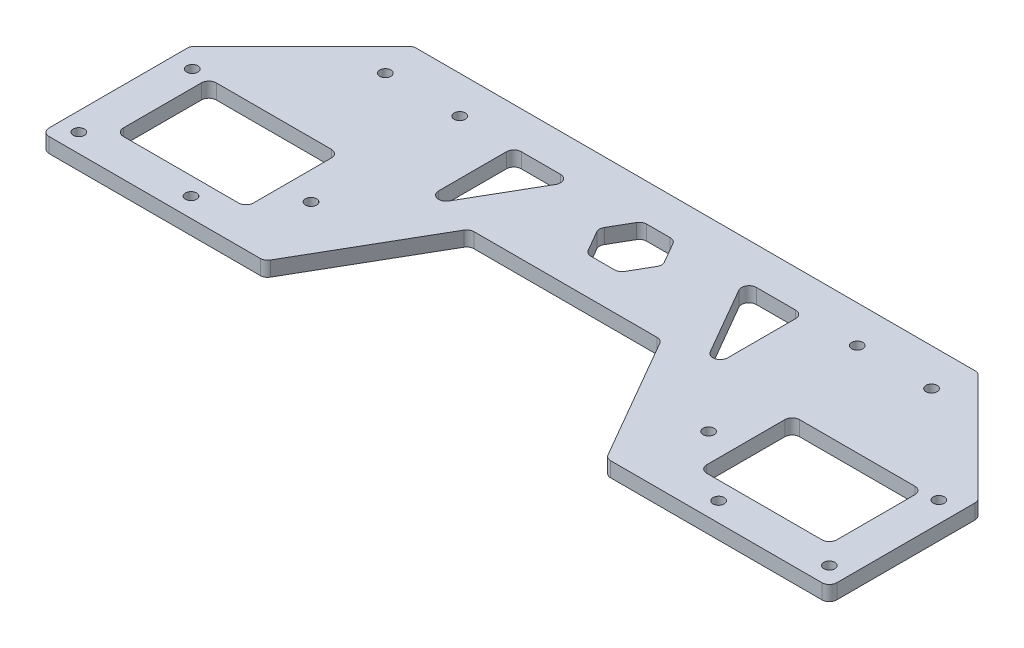
SolidWorks part; units mm, degrees
ref_plane "前视基准面" through (0, 0, 0) normal (0, 0, 1) x (1, 0, 0)
ref_plane "上视基准面" through (0, 0, 0) normal (0, 1, 0) x (1, 0, 0)
ref_plane "右视基准面" through (0, 0, 0) normal (1, 0, 0) x (0, 0, -1)
sketch "草图1" plane through (0, 0, 0) normal (0, 1, 0) x (1, 0, 0)
  line L0 (0, 0) -> (51.5855, 0)
  line L1 (51.5855, 0) -> (71.7927, -35)
  line L2 (71.7927, -35) -> (131.7927, -35)
  line L3 (131.7927, -35) -> (131.7927, 5)
  line L4 (131.7927, 5) -> (101.7927, 35)
  line L5 (101.7927, 35) -> (-50.2073, 35)
  line L6 (-50.2073, 35) -> (-80.2073, 5)
  line L7 (-80.2073, 5) -> (-80.2073, -35)
  line L8 (-80.2073, -35) -> (-20.2073, -35)
  line L9 (-20.2073, -35) -> (0, 0)
  dimension "D2" = 60
  dimension "D3" = 60
  dimension "D4" = 35
  dimension "D5" = 60
  dimension "D6" = 60
  dimension "D7" = 45
  dimension "D8" = 45
  dimension "D9" = 30
  dimension "D10" = 30
  dimension "D11" = 35
  dimension "D12" = 35
  dimension "D13" = 92
extrude "凸台-拉伸1" add sketch "草图1" along normal blind 4
sketch "草图2" plane through (0, 4, 0) normal (0, 1, 0) x (1, 0, 0)
  line L0 (-80.2073, -35) -> (-20.2073, -35) construction
  line L1 (-70.2073, -25) -> (-35.2073, -25)
  line L2 (-70.2073, -25) -> (-70.2073, 0)
  line L3 (-70.2073, 0) -> (-35.2073, 0)
  line L4 (-35.2073, -25) -> (-35.2073, 0)
  line L5 (121.7927, -25) -> (86.7927, -25)
  line L6 (121.7927, -25) -> (121.7927, 0)
  line L7 (121.7927, 0) -> (86.7927, 0)
  line L8 (86.7927, -25) -> (86.7927, 0)
  line L9 (-80.2073, 5) -> (-80.2073, -35) construction
  line L10 (71.7927, -35) -> (131.7927, -35) construction
  line L11 (131.7927, -35) -> (131.7927, 5) construction
  dimension "D1" = 10
  dimension "D2" = 10
  dimension "D3" = 10
  dimension "D4" = 10
  dimension "D5" = 35
  dimension "D6" = 25
  dimension "D7" = 35
  dimension "D8" = 25
extrude "切除-拉伸1" cut sketch "草图2" against normal blind 4
sketch "草图3" plane through (0, 4, 0) normal (0, 1, 0) x (1, 0, 0)
  line L0 (-80.2073, -35) -> (-20.2073, -35) construction
  line L1 (-80.2073, 5) -> (-80.2073, -35) construction
  line L2 (25.7927, 119.2379) -> (25.7927, -49.2379) construction
  line L3 (101.7927, 35) -> (-50.2073, 35) construction
  circle A0 centre (-75.2073, -30) radius 1.5
  circle A1 centre (-45.2073, -29.7968) radius 1.5
  circle A2 centre (-74.6686, 0) radius 1.5
  circle A3 centre (126.254, 0) radius 1.5
  circle A4 centre (96.7927, -29.7968) radius 1.5
  circle A5 centre (126.7927, -30) radius 1.5
  circle A6 centre (-27.7073, -15) radius 1.5
  circle A7 centre (-47.7073, 25) radius 1.5
  circle A8 centre (-27.7073, 25) radius 1.5
  circle A9 centre (79.2927, -15) radius 1.5
  circle A10 centre (99.2927, 25) radius 1.5
  circle A11 centre (79.2927, 25) radius 1.5
  point P32 (25.7927, 35)
  point P33 (25.7927, 35)
  dimension "D1" = 5
  dimension "D2" = 5
  dimension "D3" = 30
  dimension "D4" = 30
  dimension "D5" = 20
  dimension "D6" = 52.5
  dimension "D7" = 3
  dimension "D9" = 10
  dimension "D10" = 20
  dimension "D11" = 32.5
  dimension "D8" = 10
extrude "切除-拉伸2" cut sketch "草图3" against normal blind 4
sketch "草图4" plane through (0, 4, 0) normal (0, 1, 0) x (1, 0, 0)
  line L0 (0, 0) -> (51.5855, 0) construction
  line L1 (34.453, 17.5) -> (30.1229, 25)
  line L2 (30.1229, 25) -> (21.4626, 25)
  line L3 (21.4626, 25) -> (17.1325, 17.5)
  line L4 (17.1325, 17.5) -> (21.4626, 10)
  line L5 (21.4626, 10) -> (30.1229, 10)
  line L6 (30.1229, 10) -> (34.453, 17.5)
  line L7 (101.7927, 35) -> (-50.2073, 35) construction
  line L8 (48.6987, 25) -> (64.6987, 25)
  line L9 (64.6987, -2.7128) -> (48.6987, 25)
  line L10 (64.6987, 25) -> (64.6987, -2.7128)
  line L11 (51.5855, 0) -> (71.7927, -35) construction
  line L12 (25.7927, 74.7356) -> (25.7927, -40.8365) construction
  line L13 (-13.1132, 25) -> (-13.1132, -2.7128)
  line L14 (-13.1132, -2.7128) -> (2.8868, 25)
  line L15 (2.8868, 25) -> (-13.1132, 25)
  circle A0 centre (25.7927, 17.5) radius 7.5 construction
  point P12 (25.7927, 0)
  dimension "D1" = 10
  dimension "D2" = 10
  dimension "D3" = 0
  dimension "D4" = 10
  dimension "D5" = 16
extrude "切除-拉伸3" cut sketch "草图4" against normal blind 4
fillet "圆角1" radius 2 30 edges at (21.4626, 2, -10) (30.1229, 2, -10) (34.453, 2, -17.5) (30.1229, 2, -25) (21.4626, 2, -25) (17.1325, 2, -17.5) (-13.1132, 2, 2.7128) (2.8868, 2, -25) (-13.1132, 2, -25) (48.6987, 2, -25) (64.6987, 2, 2.7128) (64.6987, 2, -25) (121.7927, 2, 0) (121.7927, 2, 25) (86.7927, 2, 25) (86.7927, 2, 0) (-70.2073, 2, 0) (-70.2073, 2, 25) (-35.2073, 2, 25) (-35.2073, 2, 0) (-80.2073, 2, 35) (-80.2073, 2, -5) (-50.2073, 2, -35) (101.7927, 2, -35) (131.7927, 2, -5) (131.7927, 2, 35) (71.7927, 2, 35) (51.5855, 2, 0) (0, 2, 0) (-20.2073, 2, 35)
